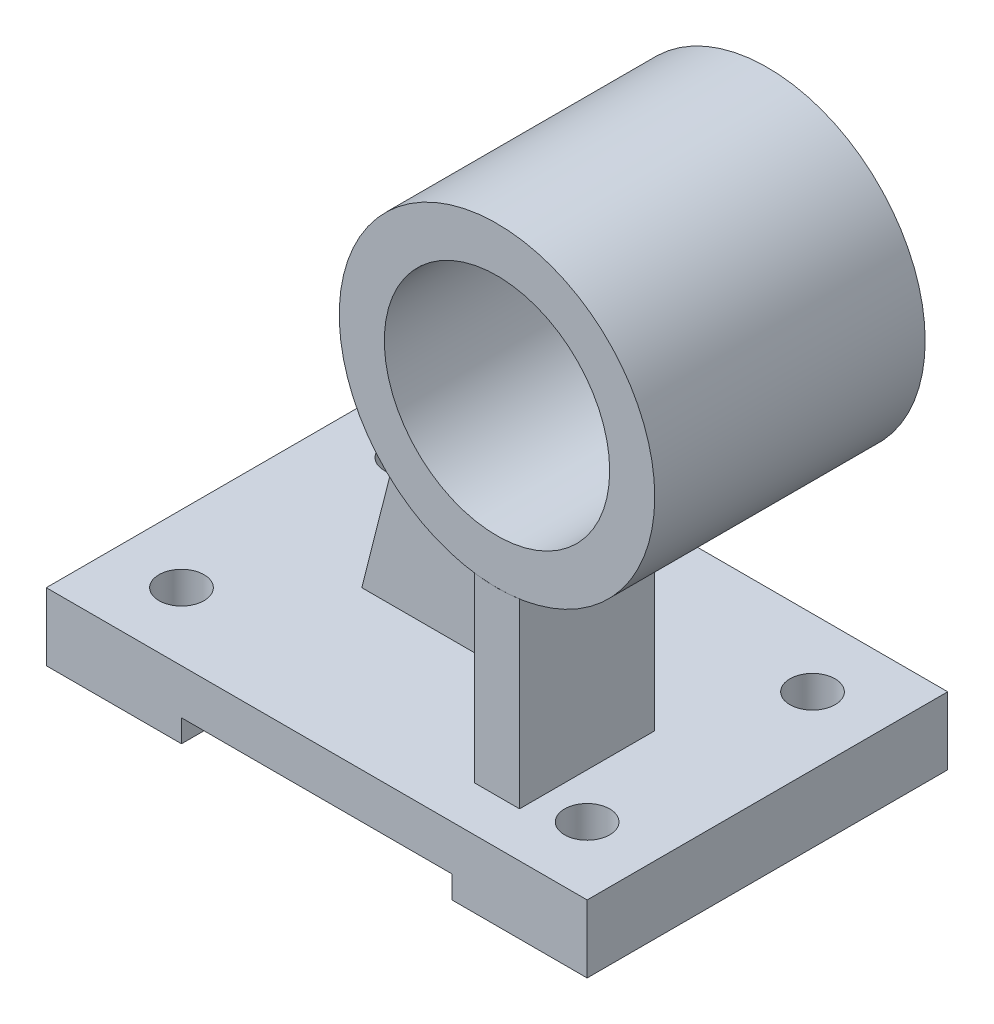
SolidWorks part; units mm, degrees
ref_plane "Front Plane" through (0, 0, 0) normal (0, 0, 1) x (1, 0, 0)
ref_plane "Top Plane" through (0, 0, 0) normal (0, 1, 0) x (1, 0, 0)
ref_plane "Right Plane" through (0, 0, 0) normal (1, 0, 0) x (0, 0, -1)
sketch "Sketch3" plane through (0, 0, 0) normal (0, 0, 1) x (1, 0, 0)
  circle A0 centre (0, 0) radius 25
  circle A1 centre (0, 0) radius 35
  dimension "D1" = 50
  dimension "D2" = 70
extrude "Boss-Extrude1" add sketch "Sketch3" against normal mid plane 60
sketch "Sketch4" plane through (0, 0, 30) normal (0, 0, 1) x (1, 0, 0)
  line L0 (0, 0) -> (0, -74.9643) construction
  line L1 (5, -74.9643) -> (-5, -74.9643)
  line L2 (5, -74.9643) -> (5, -34.641)
  line L3 (-5, -74.9643) -> (-5, -34.641)
  circle A0 centre (0, 0) radius 35 construction
  arc A1 (-5, -34.641) -> (5, -34.641) centre (0, 0) ccw
  point P6 (0, -74.9643)
  circle M3 centre (0, 0) radius 35
  dimension "D1" = 10
extrude "Boss-Extrude2" add sketch "Sketch4" against normal blind 30 separate body contours L0 L3 L1 M3 | A1 L0 L1 L2
sketch "Sketch5" plane through (0, 0, 0) normal (0, 0, 1) x (1, 0, 0)
  line L0 (0, -74.9643) -> (30, -74.9643)
  line L1 (5, -74.9643) -> (-5, -74.9643) construction
  line L2 (30, -74.9643) -> (30, -89.9643)
  line L3 (30, -89.9643) -> (0, -89.9643)
  line L4 (0, -89.9643) -> (0, -84.9643)
  line L5 (0, -84.9643) -> (-60, -84.9643)
  line L6 (-60, -84.9643) -> (-60, -89.9643)
  line L7 (-60, -89.9643) -> (-90, -89.9643)
  line L8 (-90, -89.9643) -> (-90, -74.9643)
  line L9 (-90, -74.9643) -> (0, -74.9643)
  dimension "D1" = 30
  dimension "D2" = 60
  dimension "D3" = 30
  dimension "D4" = 15
  dimension "D5" = 15
  dimension "D6" = 5
extrude "Boss-Extrude3" add sketch "Sketch5" along normal mid plane 80
sketch "Sketch6" plane through (0, 0, 0) normal (0, 0, 1) x (1, 0, 0)
  line L0 (-5, -74.9643) -> (-55, -74.9643)
  line L1 (30, -74.9643) -> (-90, -74.9643) construction
  line L2 (-5, -34.641) -> (-5, -74.9643)
  line L3 (-55, -74.9643) -> (-34.4886, 5.9614)
  circle A0 centre (0, 0) radius 35 construction
  arc A1 (-5, -34.641) -> (-34.4886, 5.9614) centre (0, 0) cw
  dimension "D1" = 35
extrude "Boss-Extrude4" add sketch "Sketch6" along normal mid plane 10 separate body contours L2 A1 L3 L0
sketch "Sketch9" plane through (0, -74.9643, 0) normal (0, 1, 0) x (1, 0, 0)
  line L0 (-30, 40) -> (-30, -40) construction
  line L1 (30, 40) -> (-90, 40) construction
  line L2 (30, -40) -> (-90, -40) construction
  line L3 (-75, -25) -> (-75, 25) construction
  line L4 (-90, -40) -> (-90, 40) construction
  circle A0 centre (-75, 25) radius 5
  circle A1 centre (-75, -25) radius 5
  circle A2 centre (15, -25) radius 5
  circle A3 centre (15, 25) radius 5
  point P9 (-75, 0)
  dimension "D3" = 10
  dimension "D4" = 10
  dimension "D1" = 50
  dimension "D2" = 15
extrude "Cut-Extrude1" cut sketch "Sketch9" against normal through all
